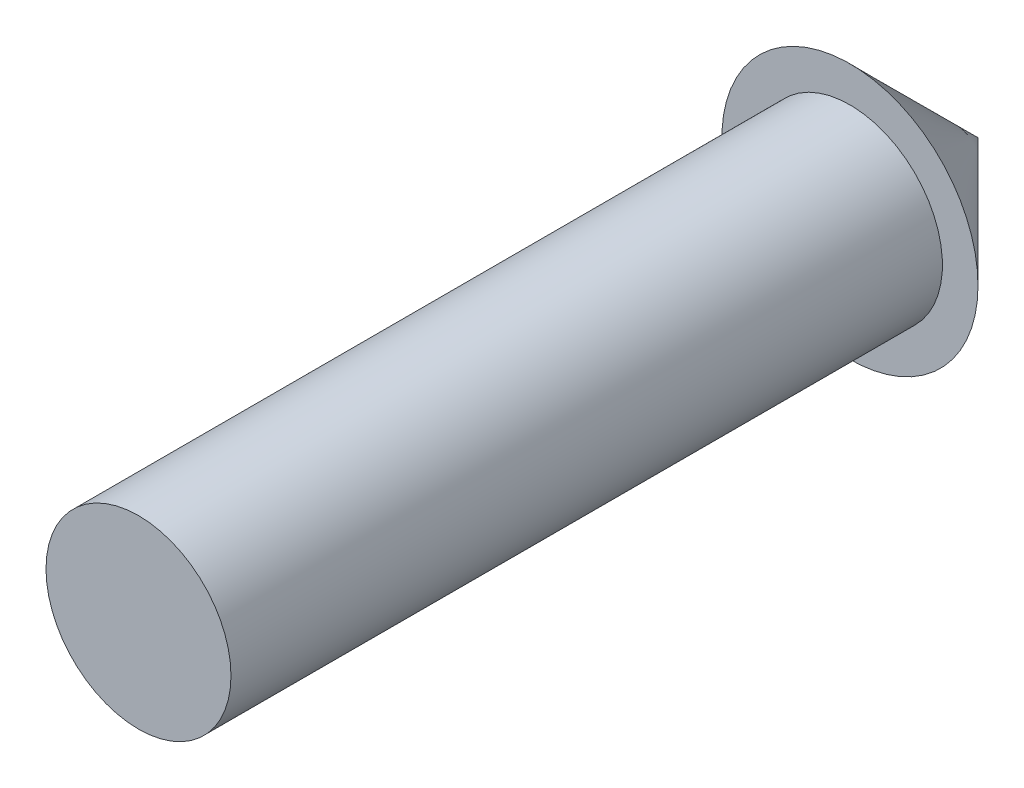
SolidWorks part; units mm, degrees
ref_plane "Front" through (0, 0, 0) normal (0, 0, 1) x (1, 0, 0)
ref_plane "Top" through (0, 0, 0) normal (0, 1, 0) x (1, 0, 0)
ref_plane "Right" through (0, 0, 0) normal (1, 0, 0) x (0, 0, -1)
sketch "Sketch2" plane through (0, 0, 0) normal (0, 1, 0) x (1, 0, 0)
  line L0 (-18, 0) -> (0, 0)
  line L1 (0, 0) -> (0, 18)
  line L2 (0, 18) -> (-18, 0)
revolve "Revolve1" add sketch "Sketch2" angle 360 about L1
sketch "Sketch3" plane through (0, 0, 0) normal (0, 0, 1) x (1, 0, 0)
  circle A0 centre (0, 0) radius 13
extrude "Extrude2" add sketch "Sketch3" along normal blind 100
